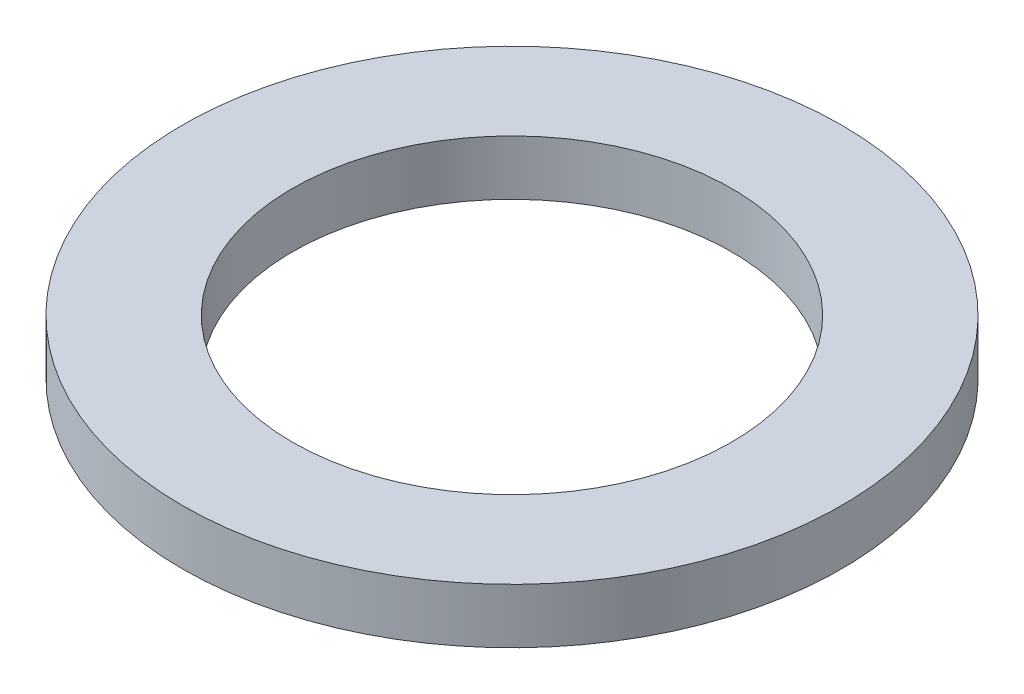
SolidWorks part; units mm, degrees
material "AISI 304"
ref_plane "前视基准面" through (0, 0, 0) normal (0, 0, 1) x (1, 0, 0)
ref_plane "上视基准面" through (0, 0, 0) normal (0, 1, 0) x (1, 0, 0)
ref_plane "右视基准面" through (0, 0, 0) normal (1, 0, 0) x (0, 0, -1)
other "Configuration Table"
sketch "草图1" plane through (0, 0, 0) normal (0, 1, 0) x (1, 0, 0)
  circle A0 centre (0, 0) radius 20
  circle A1 centre (0, 0) radius 30
  dimension "D1" = 40
  dimension "D2" = 60
extrude "凸台-拉伸1" add sketch "草图1" along normal blind 5
